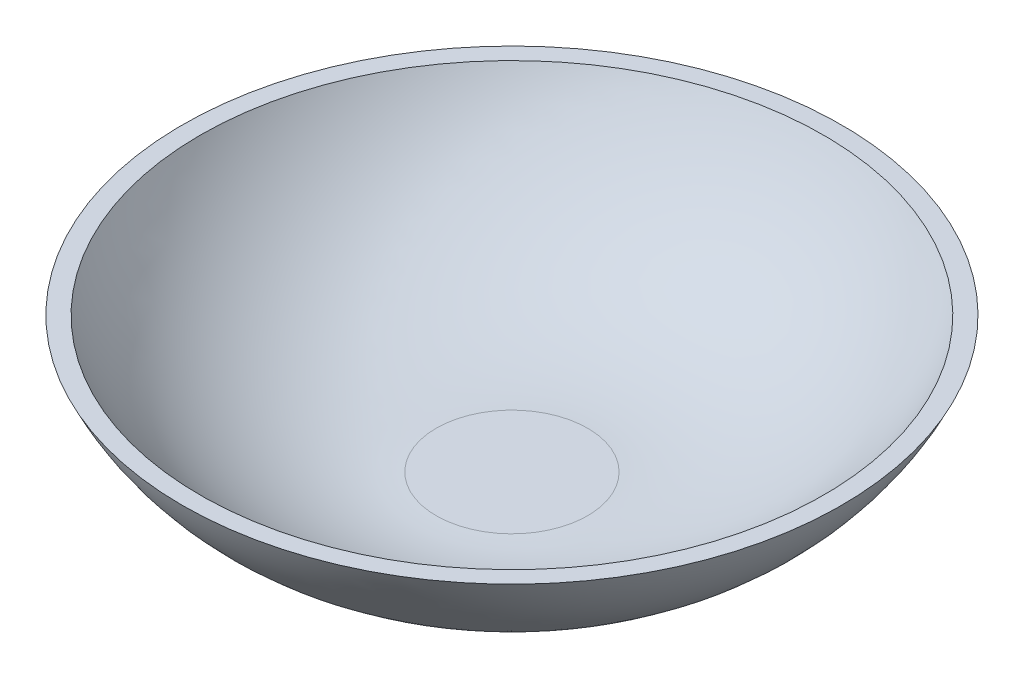
SolidWorks part; units mm, degrees
ref_plane "Спереди" through (0, 0, 0) normal (0, 0, 1) x (1, 0, 0)
ref_plane "Сверху" through (0, 0, 0) normal (0, 1, 0) x (1, 0, 0)
ref_plane "Справа" through (0, 0, 0) normal (1, 0, 0) x (0, 0, -1)
sketch "Эскиз1" plane through (0, 0, 0) normal (0, 1, 0) x (1, 0, 0)
  circle A0 centre (0, 0) radius 47.5
  dimension "D1" = 95
ref_plane "Плоскость4" through (0, 25, 0) normal (0, 1, 0) x (1, 0, 0)
sketch "Эскиз2" plane through (0, 25, 0) normal (0, 1, 0) x (1, 0, 0)
  circle A0 centre (0, 0) radius 52.5
  dimension "D1" = 105
sketch "Эскиз3" plane through (0, 0, 0) normal (0, 0, 1) x (1, 0, 0)
  line L1 (0, 0) -> (16.5, 0)
  line L2 (47.5, 0) -> (-47.5, 0) construction
  line L5 (0, 25) -> (0, 0)
  line L6 (0, 25) -> (55.5, 25)
  arc A1 (16.5, 0) -> (55.5, 25) centre (16.2054, 43.3796) ccw
revolve "Повернуть1" add sketch "Эскиз3" angle 360 about L5
sketch "Эскиз6" plane through (0, 0, 0) normal (0, 0, 1) x (1, 0, 0)
  line L0 (0, 2.1246) -> (12.7619, 2.1246)
  line L1 (0, 25) -> (0, 2.1246)
  line L2 (0, 25) -> (52.5, 25)
  line L3 (52.5, 25) -> (-52.5, 25) construction
  line L4 (55.5, 25) -> (-55.5, 25) construction
  arc A0 (12.7619, 2.1246) -> (52.5, 25) centre (14.2578, 45.4793) ccw
revolve "Вырез-Повернуть1" cut sketch "Эскиз6" angle 360 about L1
